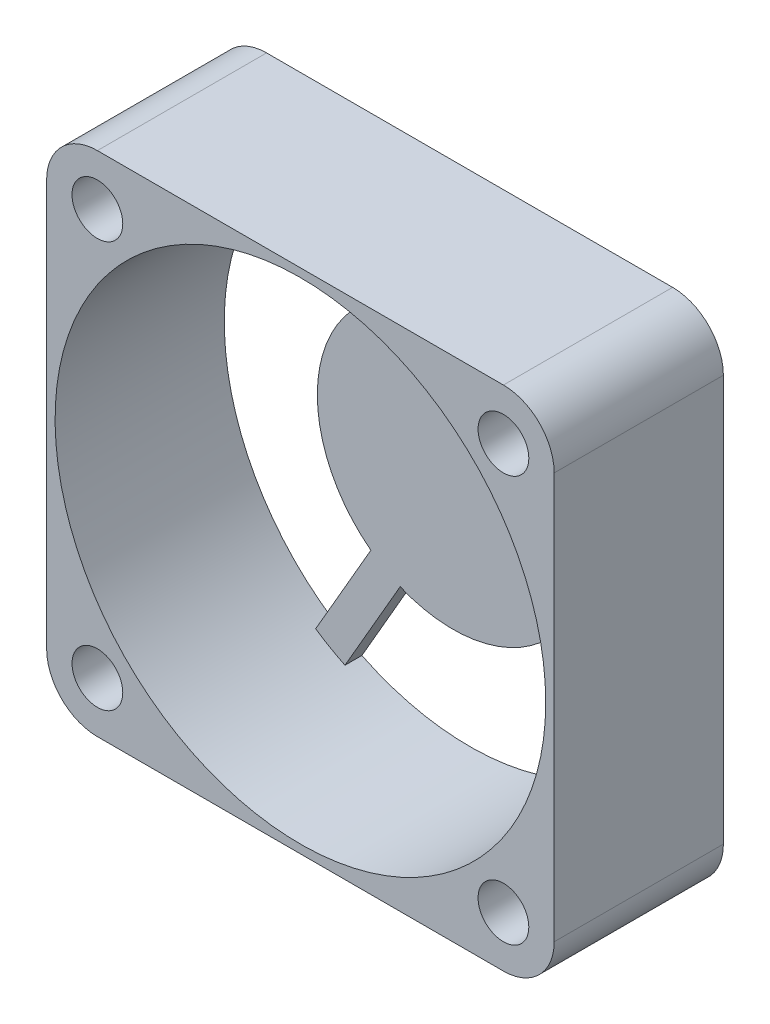
SolidWorks part; units mm, degrees
material "ABS"
ref_plane "Přední rovina" through (0, 0, 0) normal (0, 0, 1) x (1, 0, 0)
ref_plane "Horní rovina" through (0, 0, 0) normal (0, 1, 0) x (1, 0, 0)
ref_plane "Pravá rovina" through (0, 0, 0) normal (1, 0, 0) x (0, 0, -1)
sketch "Skica1" plane through (0, 0, 0) normal (0, 0, 1) x (1, 0, 0)
  line L0 (-15, 0) -> (-15, 12)
  line L1 (12, -15) -> (-12, -15)
  line L2 (15, -12) -> (15, 12)
  line L3 (12, 15) -> (-12, 15)
  line L4 (-15, -12) -> (-15, 12)
  line L5 (15, -15) -> (-15, 15) construction
  line L6 (15, 15) -> (-15, -15) construction
  line L7 (0, 15) -> (-12, 15) construction
  line L8 (-12, 12) -> (-15, 12) construction
  circle A0 centre (0, 0) radius 14.5
  circle A1 centre (-12, 12) radius 1.5
  circle A2 centre (12, 12) radius 1.5
  circle A3 centre (12, -12) radius 1.5
  circle A4 centre (-12, -12) radius 1.5
  arc A5 (-15, -12) -> (-12, -15) centre (-12, -12) ccw
  arc A6 (15, -12) -> (12, -15) centre (12, -12) cw
  arc A7 (15, 12) -> (12, 15) centre (12, 12) ccw
  arc A8 (-12, 15) -> (-15, 12) centre (-12, 12) ccw
  dimension "D1" = 2
  dimension "D3" = 3
  dimension "D4" = 29
  dimension "D5" = 24
  dimension "D6" = 30
  dimension "D2" = 2
extrude "Přidat vysunutím1" add sketch "Skica1" along normal blind 10 contours L3 A8 L0 L4 A5 L1 A6 L2 A7 A0 A1 A2 A3 A4
sketch "Skica2" plane through (0, 0, 0) normal (0, 0, 1) x (1, 0, 0)
  line L0 (8, 0) -> (14.5, 0) construction
  line L1 (11.25, 0) -> (11.25, 1) construction
  line L2 (7.9373, 1) -> (14.4655, 1)
  line L3 (7.9373, -1) -> (14.4655, -1)
  line L4 (-3.1026, -7.3739) -> (-6.3667, -13.0275)
  line L5 (-4.8347, -6.3739) -> (-8.0988, -12.0275)
  line L6 (-4.8347, 6.3739) -> (-8.0988, 12.0275)
  line L7 (-3.1026, 7.3739) -> (-6.3667, 13.0275)
  circle A0 centre (0, 0) radius 8
  circle A1 centre (0, 0) radius 14.5 construction
  circle A2 centre (0, 0) radius 14.5
  point P25 (0, 0)
  dimension "D1" = 16
  dimension "D2" = 3
extrude "Přidat vysunutím2" add sketch "Skica2" along normal blind 1 contours L7 A2 L6 A0 | A0 | L3 A2 L2 A0 | L5 A2 L4 A0
